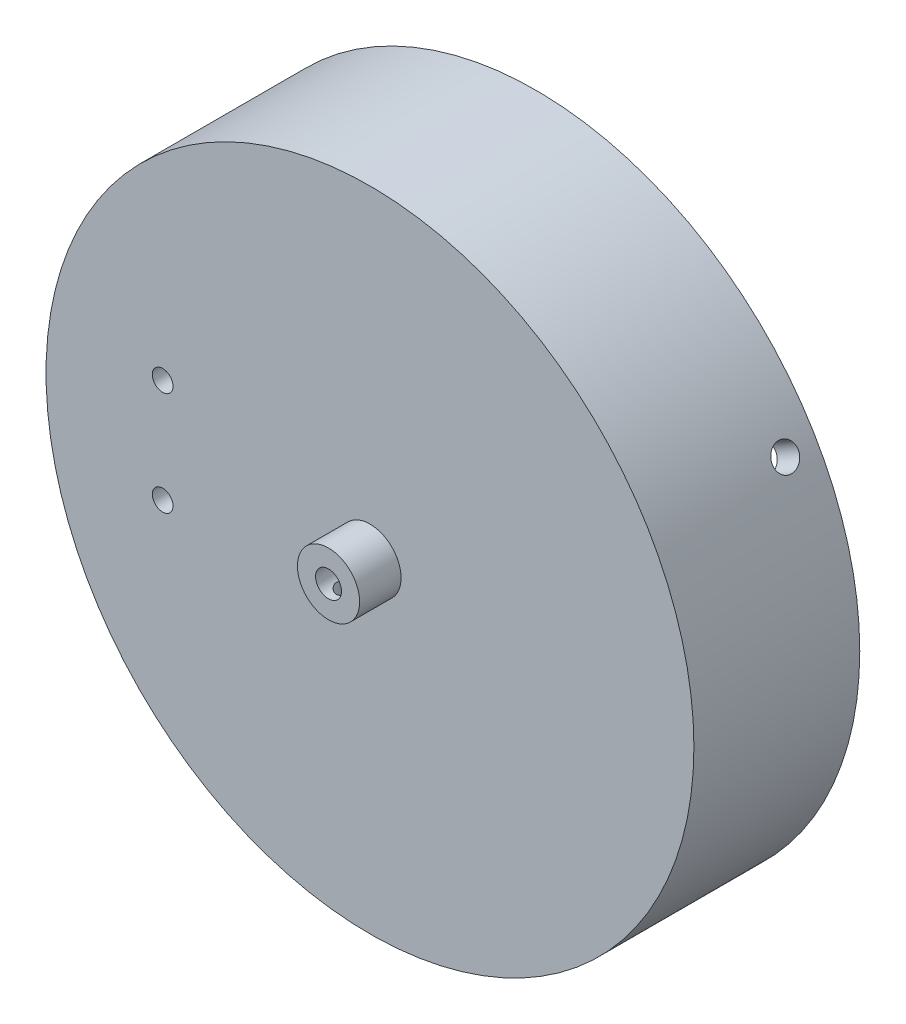
SolidWorks part; units mm, degrees
material "Perspex (TM) GS Acrylic Cast Sheet"
ref_plane "Front Plane" through (0, 0, 0) normal (0, 0, 1) x (1, 0, 0)
ref_plane "Top Plane" through (0, 0, 0) normal (0, 1, 0) x (1, 0, 0)
ref_plane "Right Plane" through (0, 0, 0) normal (1, 0, 0) x (0, 0, -1)
sketch "Sketch1" plane through (0, 0, 0) normal (0, 0, 1) x (1, 0, 0)
  circle A0 centre (0, 0) radius 57.5
  circle A1 centre (0, 0) radius 62.5
  dimension "D1" = 115
  dimension "D2" = 125
extrude "Boss-Extrude1" add sketch "Sketch1" along normal blind 10
sketch "Sketch2" plane through (0, 0, 10) normal (0, 0, 1) x (1, 0, 0)
  circle A0 centre (0, 0) radius 62.5
  circle A1 centre (0, 0) radius 62.5 construction
extrude "Boss-Extrude2" add sketch "Sketch2" along normal blind 22
sketch "Sketch3" plane through (0, 0, 10) normal (0, 0, -1) x (-1, 0, 0)
  circle A0 centre (0, 0) radius 2.5
  dimension "D1" = 5
extrude "Cut-Extrude1" cut sketch "Sketch3" against normal through all
sketch "Sketch4" plane through (0, 0, 10) normal (0, 0, -1) x (-1, 0, 0)
  line L1 (0, 16) -> (74.6597, 16)
  line L3 (0, -16) -> (74.6597, -16)
  line L4 (74.6597, 16) -> (74.6597, -16)
  arc A0 (0, 16) -> (0, -16) centre (0, 0) ccw
  dimension "D1" = 32
extrude "Cut-Extrude2" cut sketch "Sketch4" against normal blind 18
sketch "Sketch5" plane through (0, 0, 32) normal (0, 0, 1) x (1, 0, 0)
  circle A0 centre (0, 0) radius 6
  circle A1 centre (0, 0) radius 2.5 construction
  circle A2 centre (0, 0) radius 2.5
  dimension "D1" = 12
extrude "Boss-Extrude3" add sketch "Sketch5" along normal blind 8
sketch "Sketch6" plane through (0, 0, 0) normal (0, 1, 0) x (1, 0, 0)
  line L0 (-62.5, -32) -> (62.5, -32) construction
  line L1 (0, -37) -> (0, -40) construction
  line L2 (-6, -40) -> (6, -40) construction
  circle A0 centre (0, -37) radius 1.5
  dimension "D1" = 3
  dimension "D2" = 5
extrude "Cut-Extrude3" cut sketch "Sketch6" against normal through all
sketch "Sketch7" plane through (0, 0, 0) normal (0, 1, 0) x (1, 0, 0)
  line L0 (57.5, 0) -> (-57.5, 0) construction
  line L1 (0, 0) -> (0, -6) construction
  circle A0 centre (0, -6) radius 2.5
  dimension "D1" = 5
  dimension "D2" = 6
extrude "Cut-Extrude4" cut sketch "Sketch7" against normal through all
pattern_circular "CirPattern1" count 3 over 360 about axis through (0, 0, 0) along (0, 0, 1) of "Cut-Extrude4"
sketch "Sketch8" plane through (0, 0, 28) normal (0, 0, -1) x (-1, 0, 0)
  line L0 (0, 0) -> (40, 0) construction
  line L1 (40, 10) -> (40, -10) construction
  circle A0 centre (40, 10) radius 2
  circle A1 centre (40, -10) radius 2
  dimension "D3" = 4
  dimension "D1" = 20
  dimension "D2" = 40
extrude "Cut-Extrude5" cut sketch "Sketch8" against normal through all
